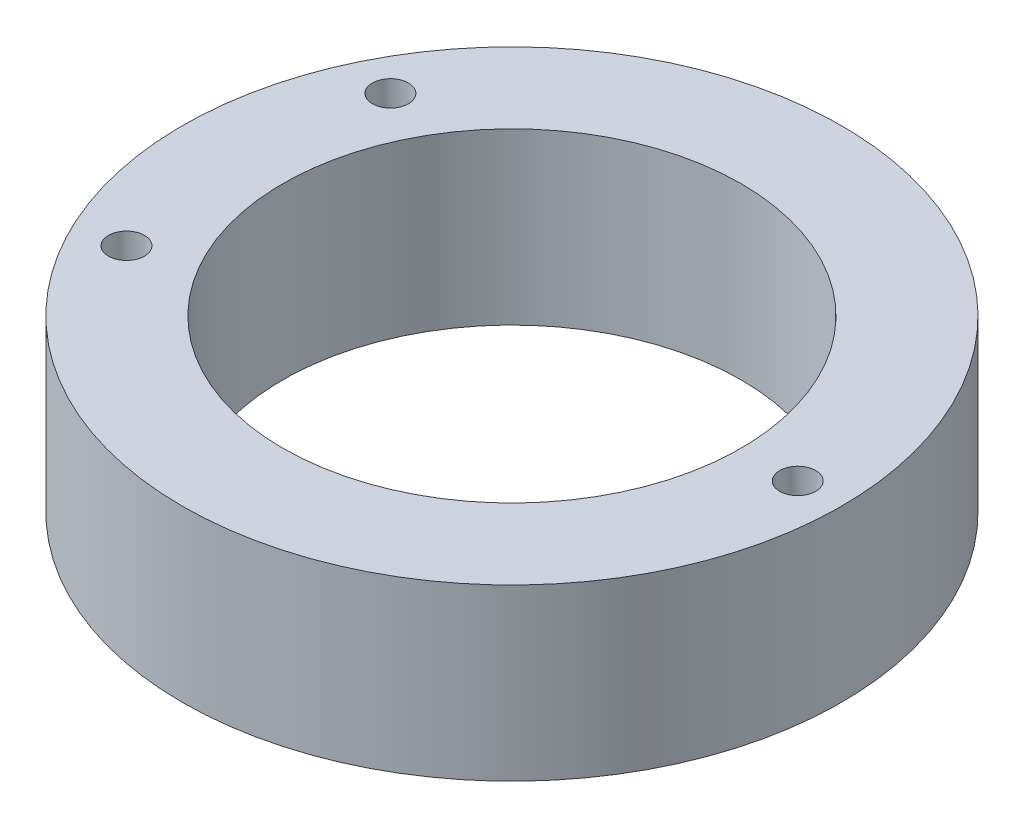
SolidWorks part; units mm, degrees
ref_plane "前视基准面" through (0, 0, 0) normal (0, 0, 1) x (1, 0, 0)
ref_plane "上视基准面" through (0, 0, 0) normal (0, 1, 0) x (1, 0, 0)
ref_plane "右视基准面" through (0, 0, 0) normal (1, 0, 0) x (0, 0, -1)
sketch "草图1" plane through (0, 0, 0) normal (0, 1, 0) x (1, 0, 0)
  line L0 (-24.6146, 12.8135) -> (0, 0) construction
  line L1 (0, 0) -> (-24.6146, -12.8135) construction
  line L2 (0, 0) -> (27.75, 0) construction
  line L3 (-24.6146, 12.8135) -> (-24.6146, -12.8135) construction
  circle A0 centre (0, 0) radius 22.25
  circle A1 centre (0, 0) radius 32
  circle A2 centre (27.75, 0) radius 1.75
  circle A3 centre (-24.6146, 12.8135) radius 1.75
  circle A4 centre (-24.6146, -12.8135) radius 1.75
  dimension "D1" = 44.5
  dimension "D2" = 64
  dimension "D5" = 3.5
  dimension "D3" = 55
  dimension "D4" = 27.75
extrude "凸台-拉伸1" add sketch "草图1" along normal blind 16.5
